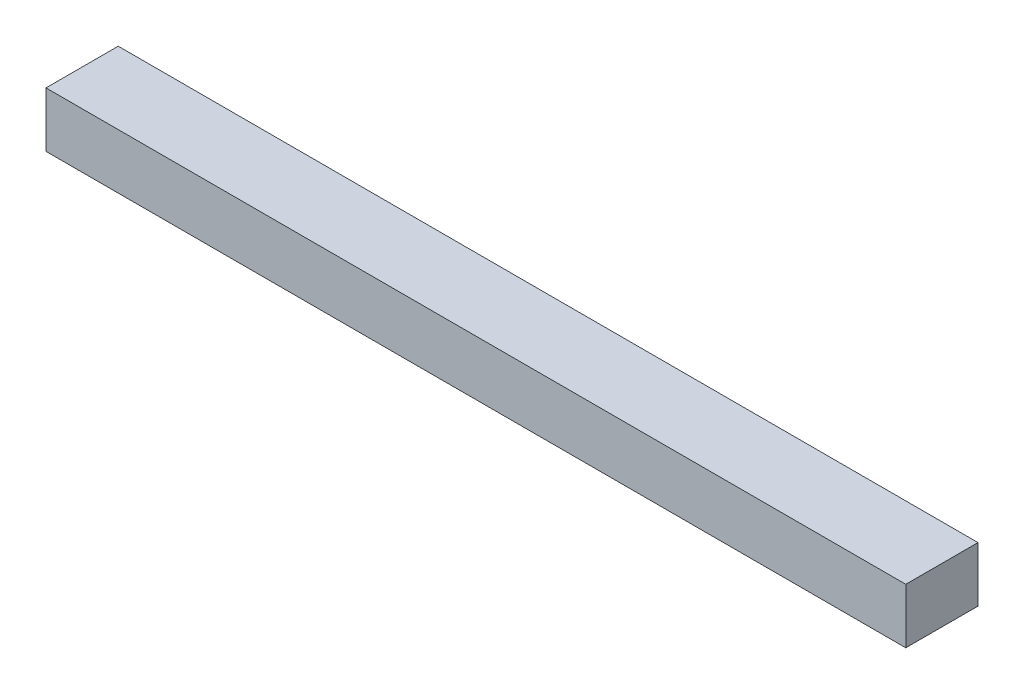
SolidWorks part; units mm, degrees
ref_plane "前视" through (0, 0, 0) normal (0, 0, 1) x (1, 0, 0)
ref_plane "上视" through (0, 0, 0) normal (0, 1, 0) x (1, 0, 0)
ref_plane "右视" through (0, 0, 0) normal (1, 0, 0) x (0, 0, -1)
sketch "草图1" plane through (0, 0, 0) normal (0, 0, 1) x (1, 0, 0)
  line L1 (-85.0515, 139.7185) -> (2414.9485, 139.7185)
  line L2 (-85.0515, 139.7185) -> (-85.0515, -20.2815)
  line L3 (-85.0515, -20.2815) -> (2414.9485, -20.2815)
  line L4 (2414.9485, 139.7185) -> (2414.9485, -20.2815)
  dimension "D1" = 2500
  dimension "D2" = 160
extrude "基体-拉伸" add sketch "草图1" along normal blind 210
